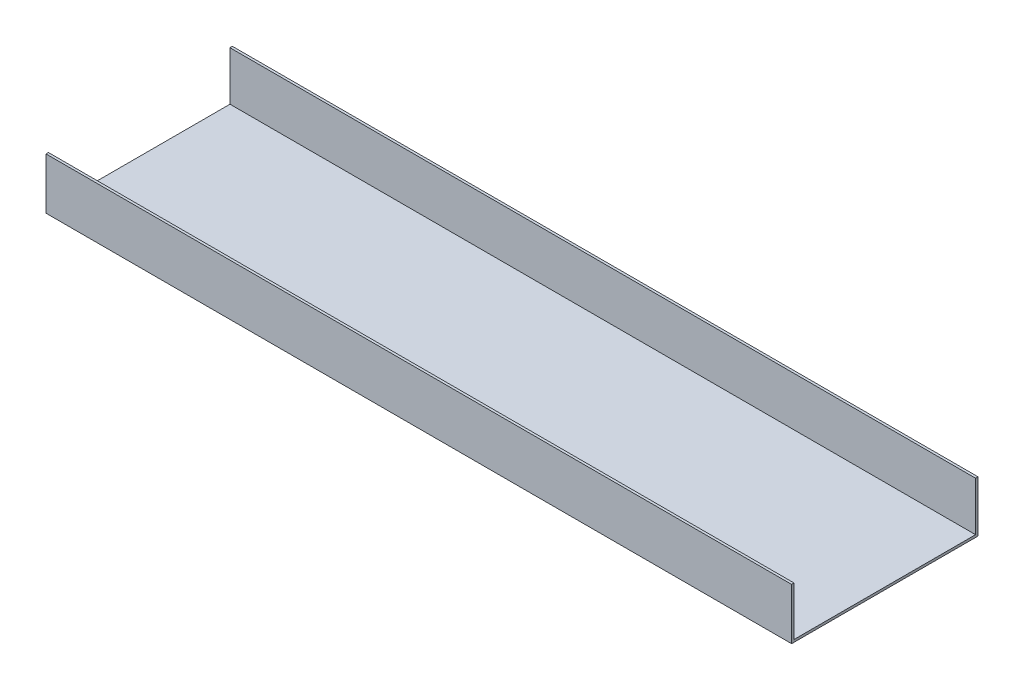
SolidWorks part; units mm, degrees
ref_plane "Front Plane" through (0, 0, 0) normal (0, 0, 1) x (1, 0, 0)
ref_plane "Top Plane" through (0, 0, 0) normal (0, 1, 0) x (1, 0, 0)
ref_plane "Right Plane" through (0, 0, 0) normal (1, 0, 0) x (0, 0, -1)
sketch "Sketch1" plane through (0, 0, 0) normal (0, 1, 0) x (1, 0, 0)
  line L1 (-152.4, 38.1) -> (152.4, 38.1)
  line L2 (-152.4, 38.1) -> (-152.4, -38.1)
  line L3 (-152.4, -38.1) -> (152.4, -38.1)
  line L4 (152.4, 38.1) -> (152.4, -38.1)
  line L5 (-152.4, 38.1) -> (152.4, -38.1) construction
  line L6 (-152.4, -38.1) -> (152.4, 38.1) construction
  point P0 (0, 0)
  dimension "D1" = 304.8
  dimension "D2" = 76.2
extrude "Boss-Extrude1" add sketch "Sketch1" along normal blind 1
sketch "Sketch2" plane through (0, 1, 0) normal (0, 1, 0) x (1, 0, 0)
  line L0 (-152.4, -37.1) -> (152.4, -37.1)
  line L1 (-152.4, 38.1) -> (-152.4, -38.1) construction
  line L2 (152.4, -38.1) -> (152.4, 38.1) construction
  line L3 (-152.4, 37.1) -> (152.4, 37.1)
  line L4 (-152.4, -38.1) -> (152.4, -38.1) construction
  line L5 (152.4, 38.1) -> (-152.4, 38.1) construction
  dimension "D1" = 1
  dimension "D2" = 1
extrude "Extrude-Thin1" add sketch "Sketch2" along normal blind 20 thin contours L0
sketch "Sketch5" plane through (0, 1, 0) normal (0, 1, 0) x (1, 0, 0)
  line L0 (-152.4, 37.1) -> (152.4, 37.1)
  line L1 (-152.4, 38.1) -> (-152.4, -37.1) construction
  line L2 (152.4, -37.1) -> (152.4, 38.1) construction
  line L3 (152.4, 38.1) -> (-152.4, 38.1) construction
  dimension "D1" = 1
extrude "Extrude-Thin2" add sketch "Sketch5" along normal blind 20 thin thin type one direction reverse wall 1
